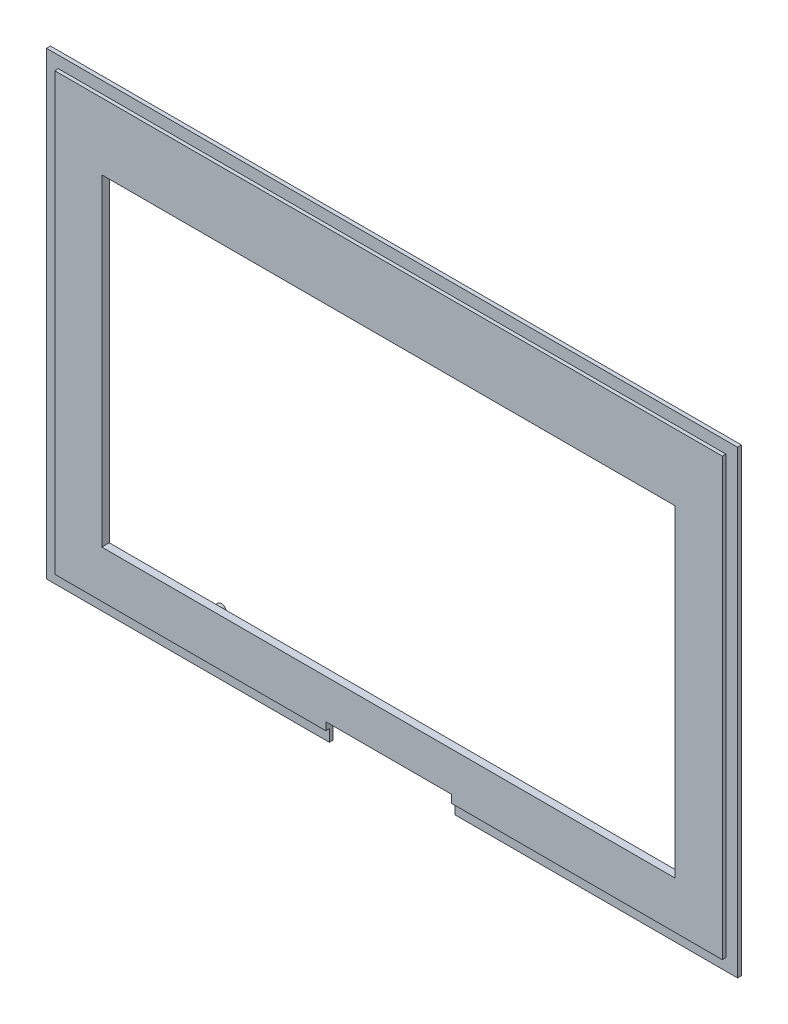
SolidWorks part; units mm, degrees
ref_plane "Plano frontal" through (0, 0, 0) normal (0, 0, 1) x (1, 0, 0)
ref_plane "Plano superior" through (0, 0, 0) normal (0, 1, 0) x (1, 0, 0)
ref_plane "Plano direito" through (0, 0, 0) normal (1, 0, 0) x (0, 0, -1)
sketch "Esboço1" plane through (0, 0, 0) normal (0, 0, 1) x (1, 0, 0)
  line L0 (11, 65.5) -> (171, 65.5) construction
  line L1 (0, 0) -> (182, 0)
  line L2 (0, 0) -> (0, 131)
  line L3 (0, 131) -> (182, 131)
  line L4 (182, 0) -> (182, 131)
  line L5 (11, 113.5) -> (171, 113.5)
  line L6 (11, 113.5) -> (11, 17.5)
  line L7 (11, 17.5) -> (171, 17.5)
  line L8 (171, 113.5) -> (171, 17.5)
  line L9 (5.7, 118.4) -> (176.3, 118.4)
  line L10 (5.7, 118.4) -> (5.7, 6.8)
  line L11 (5.7, 6.8) -> (176.3, 6.8)
  line L12 (176.3, 118.4) -> (176.3, 6.8)
  line L13 (5.9, 118.2) -> (176.1, 118.2)
  line L14 (5.9, 118.2) -> (5.9, 7)
  line L15 (5.9, 7) -> (176.1, 7)
  line L16 (176.1, 118.2) -> (176.1, 7)
  line L17 (91, 131) -> (91, 0) construction
  point P21 (91, 65.5)
  point P22 (91, 65.5)
  dimension "D1" = 131
  dimension "D2" = 182
  dimension "D3" = 160
  dimension "D4" = 96
  dimension "D5" = 170.2
  dimension "D6" = 111.2
  dimension "D7" = 0.2
  dimension "D8" = 4.7
  dimension "D9" = 0.2
  dimension "D10" = 0.2
  dimension "D11" = 0.2
  dimension "D12" = 5.1
  dimension "D13" = 5.1
  dimension "D14" = 10.5
extrude "Ressalto-extrusão1" add sketch "Esboço1" along normal blind 0.9 contours L16 L15 L14 L13
sketch "Esboço4" plane through (0, 0, 0) normal (0, 0, -1) x (-1, 0, 0)
  line L1 (-179.1, 121.2) -> (-2.9, 121.2)
  line L2 (-179.1, 121.2) -> (-179.1, 4)
  line L3 (-179.1, 4) -> (-2.9, 4)
  line L4 (-2.9, 121.2) -> (-2.9, 4)
  line L8 (-176.1, 118.2) -> (-176.1, 7) construction
  line L9 (-5.9, 118.2) -> (-176.1, 118.2) construction
  line L10 (-5.9, 7) -> (-176.1, 7) construction
  line L11 (-5.9, 118.2) -> (-5.9, 7) construction
  dimension "D1" = 3
  dimension "D2" = 3
  dimension "D3" = 3
  dimension "D4" = 3
extrude "Ressalto-extrusão3" add sketch "Esboço4" along normal blind 1
sketch "Esboço5" plane through (0, 4, 0) normal (0, -1, 0) x (1, 0, 0)
  line L0 (179.1, -1) -> (2.9, -1) construction
  line L1 (75, -1) -> (107, -1)
  line L2 (75, -1) -> (75, 0.9)
  line L3 (75, 0.9) -> (107, 0.9)
  line L4 (107, -1) -> (107, 0.9)
  line L5 (5.9, 0.9) -> (176.1, 0.9) construction
  point P8 (91, -1)
  point P9 (91, -1)
  dimension "D1" = 32
extrude "Corte-extrusão3" cut sketch "Esboço5" against normal blind 5
sketch "Esboço6" plane through (0, 0, -1) normal (0, 0, -1) x (-1, 0, 0)
  line L0 (-43.3, 106.45) -> (-42.05, 106.45) construction
  line L1 (-44, 16.15) -> (-44, 14.9) construction
  line L2 (-110.15, 109) -> (-40.75, 109) construction
  line L3 (-110.15, 109) -> (-110.15, 8.4) construction
  line L4 (-110.15, 8.4) -> (-40.75, 8.4) construction
  line L5 (-40.75, 109) -> (-40.75, 8.4) construction
  line L6 (-44, 16.15) -> (-42.75, 16.15) construction
  line L7 (-43.3, 106.45) -> (-43.3, 107.7) construction
  line L8 (-108.3, 106.45) -> (-108.3, 107.7) construction
  line L9 (-108.3, 106.45) -> (-109.55, 106.45) construction
  line L10 (-108.3, 14.75) -> (-108.3, 13.5) construction
  line L11 (-108.3, 14.75) -> (-109.55, 14.75) construction
  line L12 (-75, 9) -> (-107, 9) construction
  line L13 (-108.3, 14.75) -> (-108.3, 16) construction
  circle A0 centre (-108.3, 14.75) radius 1.25
  circle A1 centre (-108.3, 106.45) radius 1.25
  circle A2 centre (-43.3, 106.45) radius 1.25
  circle A3 centre (-44, 16.15) radius 1.25
  point P22 (-91, 9)
  dimension "D1" = 2.5
  dimension "D2" = 2.5
  dimension "D3" = 2.5
  dimension "D4" = 2.5
  dimension "D5" = 100.6
  dimension "D6" = 69.4
  dimension "D7" = 6.5
  dimension "D8" = 2
  dimension "D9" = 1.3
  dimension "D10" = 1.3
  dimension "D11" = 2.6
  dimension "D12" = 0.6
  dimension "D13" = 0.6
  dimension "D14" = 5.1
  dimension "D15" = 19.15
  dimension "D16" = 9
extrude "Ressalto-extrusão4" add sketch "Esboço6" along normal blind 2.5
sketch "Esboço10" plane through (0, 0, -1) normal (0, 0, -1) x (-1, 0, 0)
  line L0 (-108.3, 106.45) -> (-107.05, 106.45) construction
  line L1 (-58.55, 108.45) -> (-45.55, 108.45)
  line L2 (-58.55, 108.45) -> (-58.55, 104.45)
  line L3 (-58.55, 104.45) -> (-45.55, 104.45)
  line L4 (-45.55, 108.45) -> (-45.55, 104.45)
  line L5 (-43.3, 106.45) -> (-44.55, 106.45) construction
  circle A0 centre (-108.3, 106.45) radius 1.25 construction
  circle A1 centre (-43.3, 106.45) radius 1.25 construction
  point P9 (-58.55, 106.45)
  dimension "D1" = 1
  dimension "D2" = 14
  dimension "D3" = 4
extrude "Corte-extrusão6" cut sketch "Esboço10" against normal blind 1.1
sketch "Esboço12" plane through (0, 0, 0.9) normal (0, 0, 1) x (1, 0, 0)
  line L0 (5.9, 118.2) -> (5.9, 7) construction
  line L1 (17.9, 101.2) -> (164.1, 101.2)
  line L2 (17.9, 101.2) -> (17.9, 19)
  line L3 (17.9, 19) -> (164.1, 19)
  line L4 (164.1, 101.2) -> (164.1, 19)
  line L5 (5.9, 7) -> (75, 7) construction
  line L6 (176.1, 118.2) -> (176.1, 7) construction
  line L7 (5.9, 118.2) -> (176.1, 118.2) construction
  dimension "D1" = 12
  dimension "D2" = 12
  dimension "D3" = 12
  dimension "D4" = 17
extrude "Corte-extrusão8" cut sketch "Esboço12" against normal blind 10
